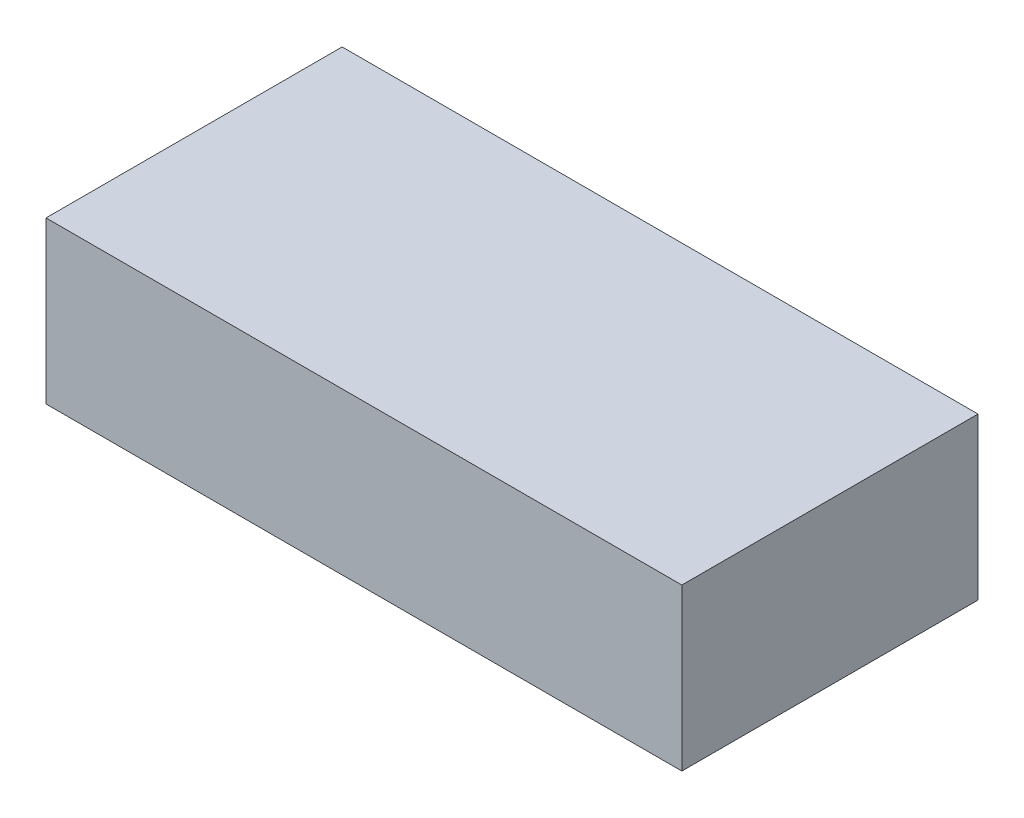
SolidWorks part; units mm, degrees
ref_plane "Front Plane" through (0, 0, 0) normal (0, 0, 1) x (1, 0, 0)
ref_plane "Top Plane" through (0, 0, 0) normal (0, 1, 0) x (1, 0, 0)
ref_plane "Right Plane" through (0, 0, 0) normal (1, 0, 0) x (0, 0, -1)
sketch "Sketch2" plane through (0, 0, 0) normal (0, 1, 0) x (1, 0, 0)
  line L1 (-36.5, -17) -> (36.5, -17)
  line L2 (-36.5, -17) -> (-36.5, 17)
  line L3 (-36.5, 17) -> (36.5, 17)
  line L4 (36.5, -17) -> (36.5, 17)
  line L5 (-36.5, -17) -> (36.5, 17) construction
  line L6 (-36.5, 17) -> (36.5, -17) construction
  point P0 (0, 0)
  dimension "D1" = 34
  dimension "D2" = 73
extrude "Boss-Extrude2" add sketch "Sketch2" along normal blind 18.5
